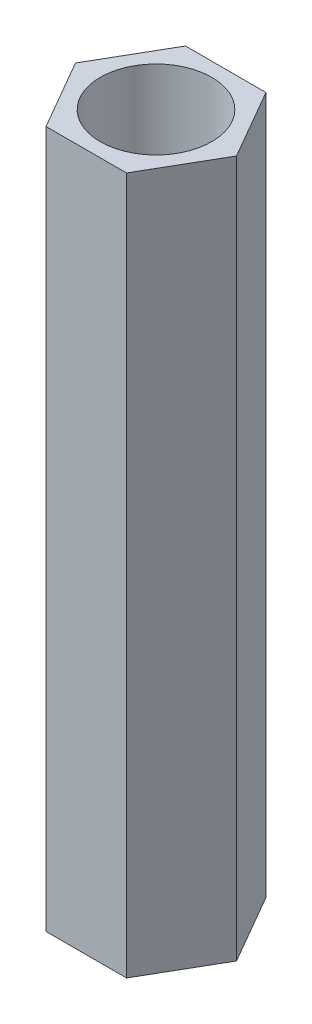
SolidWorks part; units mm, degrees
ref_plane "정면" through (0, 0, 0) normal (0, 0, 1) x (1, 0, 0)
ref_plane "윗면" through (0, 0, 0) normal (0, 1, 0) x (1, 0, 0)
ref_plane "우측면" through (0, 0, 0) normal (1, 0, 0) x (0, 0, -1)
sketch "스케치1" plane through (0, 0, 0) normal (0, 1, 0) x (1, 0, 0)
  line L1 (2.3094, 0) -> (1.1547, 2)
  line L2 (1.1547, 2) -> (-1.1547, 2)
  line L3 (-1.1547, 2) -> (-2.3094, 0)
  line L4 (-2.3094, 0) -> (-1.1547, -2)
  line L5 (-1.1547, -2) -> (1.1547, -2)
  line L6 (1.1547, -2) -> (2.3094, 0)
  circle A0 centre (0, 0) radius 1.6
  circle A1 centre (0, 0) radius 2 construction
extrude "보스-돌출2" add sketch "스케치1" along normal blind 20
